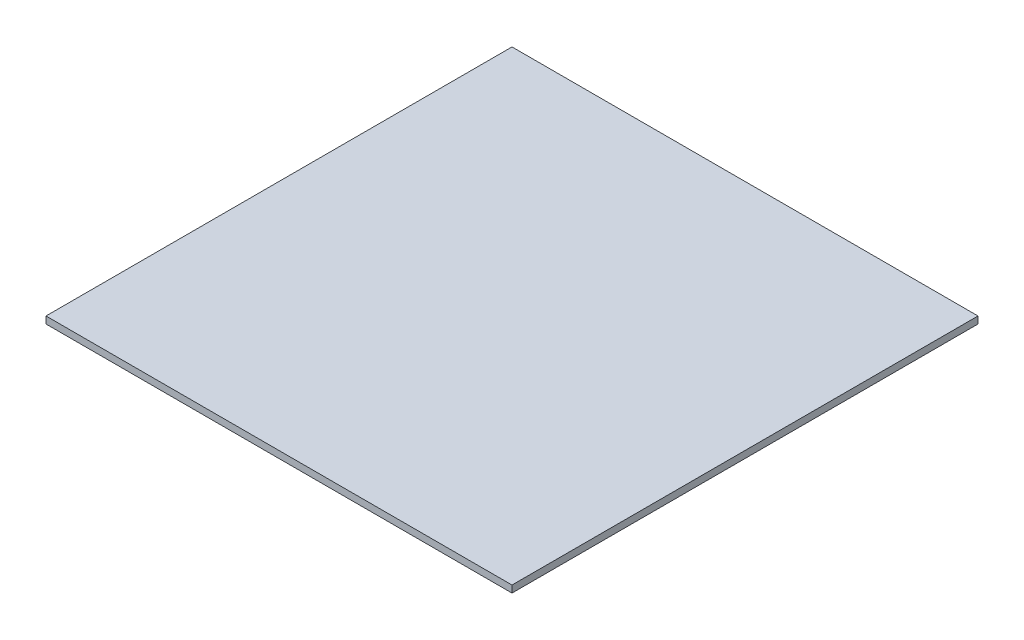
SolidWorks part; units mm, degrees
material "有机玻璃 (TM) GS 丙烯酸铸钣"
ref_plane "前视基准面" through (0, 0, 0) normal (0, 0, 1) x (1, 0, 0)
ref_plane "上视基准面" through (0, 0, 0) normal (0, 1, 0) x (1, 0, 0)
ref_plane "右视基准面" through (0, 0, 0) normal (1, 0, 0) x (0, 0, -1)
sketch "草图1" plane through (0, 0, 0) normal (0, 1, 0) x (1, 0, 0)
  line L1 (-100, 100) -> (100, 100)
  line L2 (-100, 100) -> (-100, -100)
  line L3 (-100, -100) -> (100, -100)
  line L4 (100, 100) -> (100, -100)
  line L5 (-100, 100) -> (100, -100) construction
  line L6 (-100, -100) -> (100, 100) construction
  point P0 (0, 0)
  dimension "D1" = 200
  dimension "D2" = 200
extrude "凸台-拉伸1" add sketch "草图1" along normal blind 3
